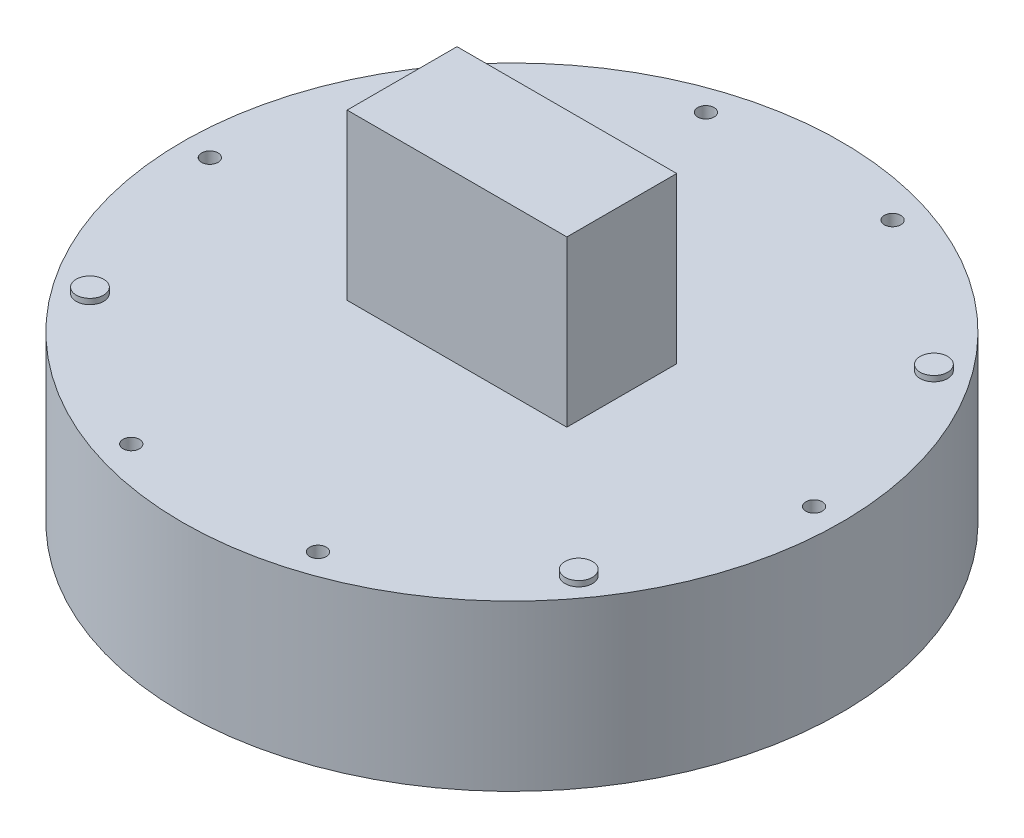
SolidWorks part; units mm, degrees
ref_plane "前视基准面" through (0, 0, 0) normal (0, 0, 1) x (1, 0, 0)
ref_plane "上视基准面" through (0, 0, 0) normal (0, 1, 0) x (1, 0, 0)
ref_plane "右视基准面" through (0, 0, 0) normal (1, 0, 0) x (0, 0, -1)
sketch "草图1" plane through (0, 0, 0) normal (0, 1, 0) x (1, 0, 0)
  circle A0 centre (0, 0) radius 60
  dimension "D1" = 120
extrude "凸台-拉伸1" add sketch "草图1" along normal blind 30
sketch "草图2" plane through (0, 30, 0) normal (0, 1, 0) x (1, 0, 0)
  circle A0 centre (0, 0) radius 55 construction
  circle A1 centre (55, 0) radius 1.5
  dimension "D1" = 110
  dimension "D2" = 3
extrude "切除-拉伸1" cut sketch "草图2" against normal blind 5
pattern_circular "阵列(圆周)1" count 10 over 360 about axis through (0, 0, 0) along (0, 1, 0) of "切除-拉伸1"
sketch "草图3" plane through (0, 30, 0) normal (0, 1, 0) x (1, 0, 0)
  line L1 (-20, 10) -> (20, 10)
  line L2 (-20, 10) -> (-20, -10)
  line L3 (-20, -10) -> (20, -10)
  line L4 (20, 10) -> (20, -10)
  line L5 (-20, 10) -> (20, -10) construction
  line L6 (-20, -10) -> (20, 10) construction
  point P0 (0, 0)
  dimension "D1" = 20
  dimension "D2" = 40
extrude "凸台-拉伸2" add sketch "草图3" along normal blind 30
sketch "草图5" plane through (0, 30, 0) normal (0, 1, 0) x (1, 0, 0)
  circle A0 centre (-44.4959, 32.3282) radius 2.5
  circle A3 centre (44.4959, -32.3282) radius 2.5
  circle A4 centre (44.4959, 32.3282) radius 2.5
  circle A5 centre (-44.4959, -32.3282) radius 2.5
  dimension "D1" = 5
extrude "凸台-拉伸4" add sketch "草图5" along normal blind 1
sketch "草图6" plane through (0, 30, 0) normal (0, 1, 0) x (1, 0, 0)
  line L1 (-35.998, 26.1541) -> (66.9875, -48.6693)
ref_plane "基准面1" through (0, 0, 0) normal (-0.5878, 0, 0.809) x (0.809, 0, 0.5878)
sketch "草图7" plane through (0, 0, 0) normal (0, -1, 0) x (1, 0, 0)
  circle A0 centre (0, 0) radius 2.5
  dimension "D1" = 5
extrude "切除-拉伸2" cut sketch "草图7" against normal blind 1
